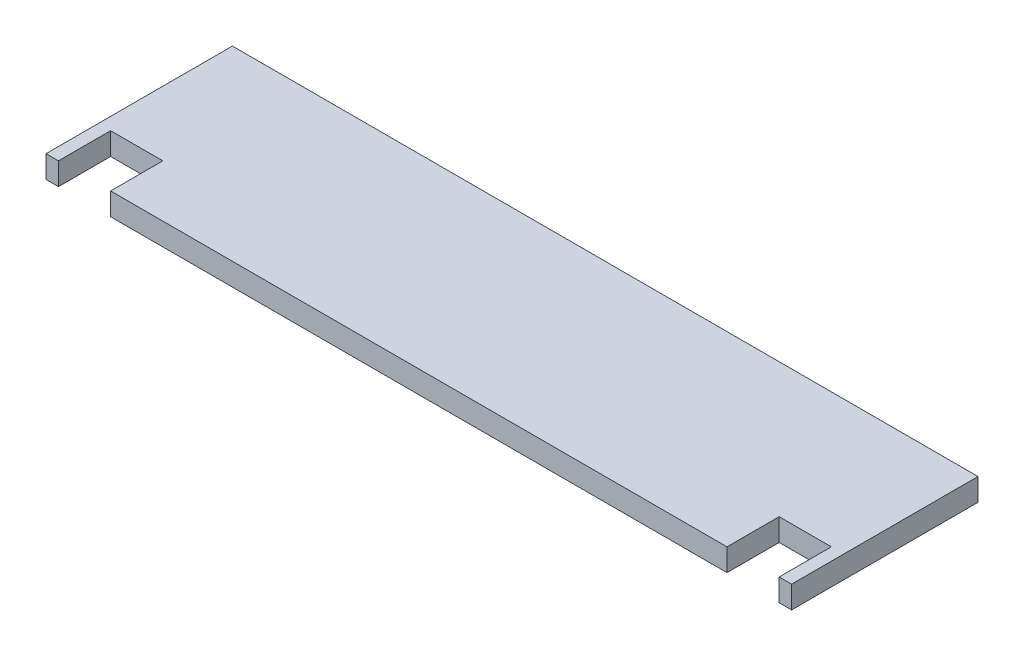
SolidWorks part; units mm, degrees
ref_plane "Plan de face" through (0, 0, 0) normal (0, 0, 1) x (1, 0, 0)
ref_plane "Plan de dessus" through (0, 0, 0) normal (0, 1, 0) x (1, 0, 0)
ref_plane "Plan de droite" through (0, 0, 0) normal (1, 0, 0) x (0, 0, -1)
sketch "Esquisse1" plane through (0, 0, 0) normal (0, 1, 0) x (1, 0, 0)
  line L1 (-300, 75) -> (300, 75)
  line L2 (-300, 75) -> (-300, -75)
  line L3 (-300, -75) -> (300, -75)
  line L4 (300, 75) -> (300, -75)
  line L5 (-300, 75) -> (300, -75) construction
  line L6 (-300, -75) -> (300, 75) construction
  point P0 (0, 0)
  dimension "D1" = 600
  dimension "D2" = 150
extrude "Boss.-Extru.1" add sketch "Esquisse1" along normal blind 18
sketch "Esquisse2" plane through (0, 18, 0) normal (0, 1, 0) x (1, 0, 0)
  line L0 (-300, 75) -> (-300, -75) construction
  line L1 (-300, 55) -> (300, 55)
  line L2 (-300, 55) -> (-300, 35)
  line L3 (-300, 35) -> (300, 35)
  line L4 (300, 55) -> (300, 35)
  line L5 (300, -75) -> (300, 75) construction
  line L6 (300, 75) -> (-300, 75) construction
  dimension "D1" = 20
  dimension "D2" = 20
sketch "Esquisse3" plane through (0, 18, 0) normal (0, 1, 0) x (1, 0, 0)
  line L0 (-290, -75) -> (-290, -33) construction
  line L1 (-300, -75) -> (300, -75) construction
  line L2 (-290, -33) -> (-300, -33) construction
  line L3 (-300, 75) -> (-300, -75) construction
  line L4 (290, -75) -> (290, -33) construction
  line L5 (290, -33) -> (300, -33) construction
  line L6 (300, -75) -> (300, 75) construction
  line L8 (-290, -33) -> (-248, -33)
  line L9 (-290, -33) -> (-290, -75)
  line L10 (-290, -75) -> (-248, -75)
  line L11 (-248, -33) -> (-248, -75)
  line L12 (290, -33) -> (248, -33)
  line L13 (290, -33) -> (290, -75)
  line L14 (290, -75) -> (248, -75)
  line L15 (248, -33) -> (248, -75)
  dimension "D5" = 42
  dimension "D6" = 42
  dimension "D1" = 10
  dimension "D2" = 42
  dimension "D3" = 10
  dimension "D4" = 42
extrude "Enlèv. mat.-Extru.1" cut sketch "Esquisse3" against normal blind 20
